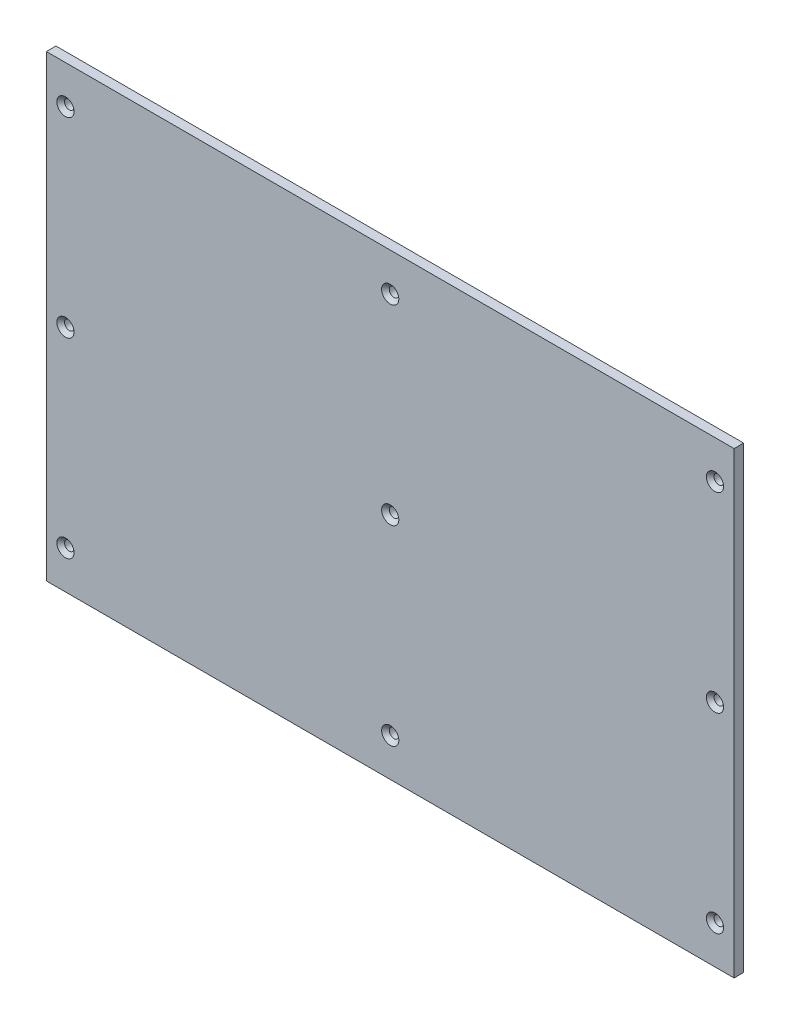
SolidWorks part; units mm, degrees
material "1.0114 (S235J0)"
ref_plane "Plan de face" through (0, 0, 0) normal (0, 0, 1) x (1, 0, 0)
ref_plane "Plan de dessus" through (0, 0, 0) normal (0, 1, 0) x (1, 0, 0)
ref_plane "Plan de droite" through (0, 0, 0) normal (1, 0, 0) x (0, 0, -1)
sketch "Esquisse1" plane through (0, 0, 0) normal (0, 0, 1) x (1, 0, 0)
  line L1 (-180, -120) -> (180, -120)
  line L2 (-180, -120) -> (-180, 120)
  line L3 (-180, 120) -> (180, 120)
  line L4 (180, -120) -> (180, 120)
  line L5 (-180, -120) -> (180, 120) construction
  line L6 (-180, 120) -> (180, -120) construction
  point P0 (0, 0)
  dimension "D1" = 360
  dimension "D2" = 240
extrude "Boss.-Extru.1" add sketch "Esquisse1" along normal blind 5
sketch "Esquisse2" plane through (0, 0, 5) normal (0, 0, 1) x (1, 0, 0)
  line L0 (-170, 120) -> (-170, -120) construction
  line L1 (180, 120) -> (-180, 120) construction
  line L2 (-180, -120) -> (180, -120) construction
  line L3 (0, 120) -> (0, -120) construction
  line L4 (170, 120) -> (170, -120) construction
  line L5 (-180, 120) -> (-180, -120) construction
  line L6 (0, 0) -> (179.0875, 0) construction
  circle A0 centre (-170, 100) radius 2.5
  circle A1 centre (-170, 0) radius 2.5
  circle A2 centre (-170, -100) radius 2.5
  circle A4 centre (0, 100) radius 2.5
  circle A5 centre (0, 0) radius 2.5
  circle A6 centre (0, -100) radius 2.5
  circle A7 centre (170, -100) radius 2.5
  circle A8 centre (170, 0) radius 2.5
  circle A9 centre (170, 100) radius 2.5
  point P30 (0, 0)
  point P31 (0, 0)
  point P33 (0, 0)
  dimension "D2" = 5
  dimension "D1" = 10
  dimension "D3" = 200
extrude "Enlèv. mat.-Extru.1" cut sketch "Esquisse2" against normal through all
chamfer "Chanfrein1" distance 2 angle 45 9 edges at (172.5, -100, 5) (172.5, 0, 5) (172.5, 100, 5) (2.5, 100, 5) (2.5, 0, 5) (2.5, -100, 5) (-167.5, -100, 5) (-167.5, 0, 5) (-167.5, 100, 5)
